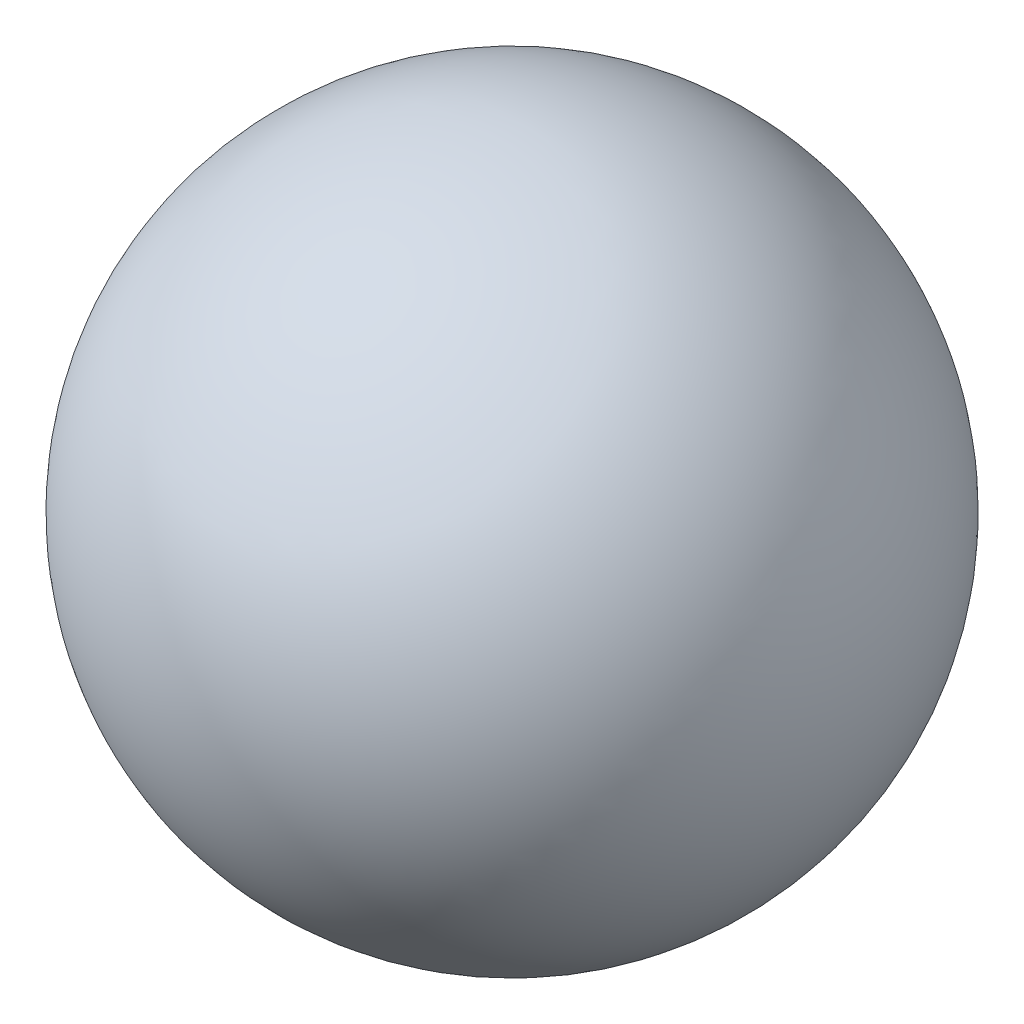
SolidWorks part; units mm, degrees
ref_plane "Front Plane" through (0, 0, 0) normal (1, 0, 0) x (0, 1, 0)
ref_plane "Top Plane" through (0, 0, 0) normal (0, 0, 1) x (0, 1, 0)
ref_plane "Right Plane" through (0, 0, 0) normal (0, 1, 0) x (-1, 0, 0)
sketch "Sketch1" plane through (0, 0, 0) normal (1, 0, 0) x (0, 1, 0)
  line L0 (0, 0) -> (0, 6.35)
  line L1 (0, 6.35) -> (0, -6.35)
  arc A0 (0, -6.35) -> (0, 6.35) centre (0, 0) ccw
  dimension "D1" = 12.7
revolve "Revolve1" add sketch "Sketch1" angle 360 about L0
